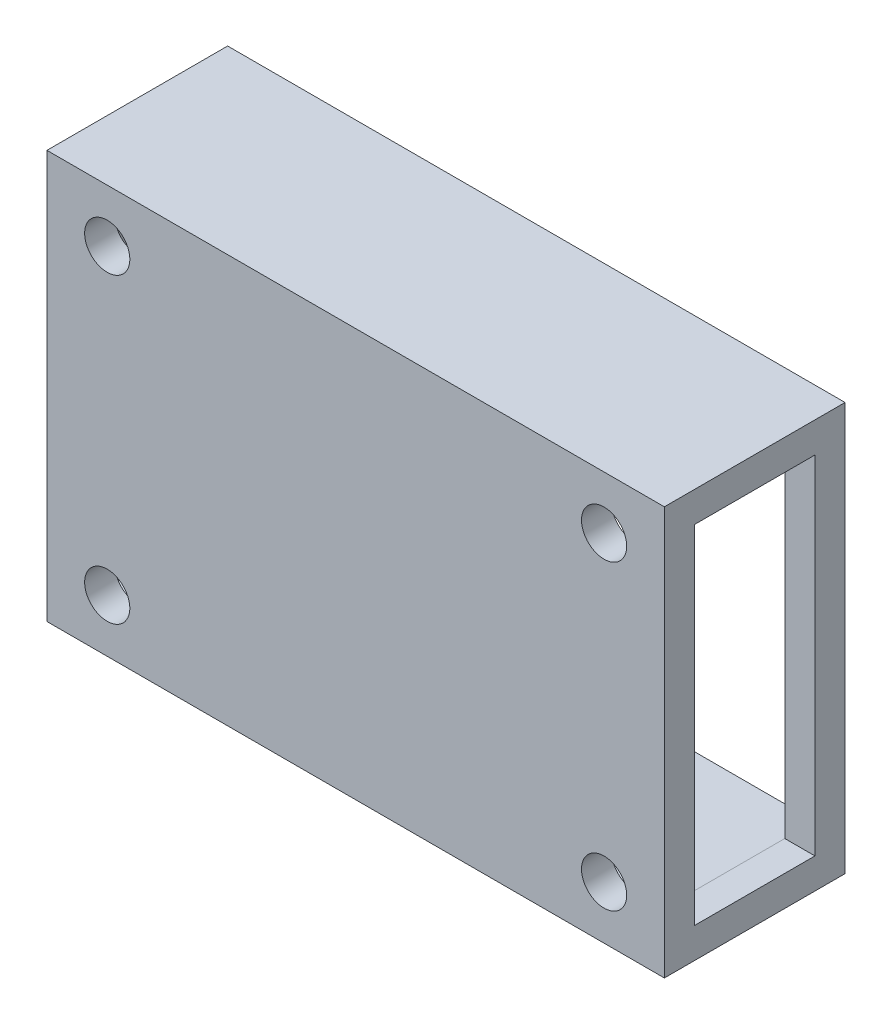
SolidWorks part; units mm, degrees
ref_plane "Plano frontal" through (0, 0, 0) normal (0, 0, 1) x (1, 0, 0)
ref_plane "Plano superior" through (0, 0, 0) normal (0, 1, 0) x (1, 0, 0)
ref_plane "Plano direito" through (0, 0, 0) normal (1, 0, 0) x (0, 0, -1)
sketch "Esboço1" plane through (0, 0, 0) normal (0, 0, 1) x (1, 0, 0)
  line L1 (0, 0) -> (35, 0)
  line L2 (0, 0) -> (0, 25.1)
  line L3 (0, 25.1) -> (35, 25.1)
  line L4 (35, 0) -> (35, 25.1)
extrude "Ressalto-extrusão1" add sketch "Esboço1" along normal blind 2
sketch "Esboço2" plane through (0, 0, 2) normal (0, 0, 1) x (1, 0, 0)
  line L0 (0, 12.55) -> (6.2733, 12.55) construction
  line L2 (0, 25.1) -> (0, 0) construction
  circle A0 centre (2.13, 22.97) radius 1.5
  circle A1 centre (2.13, 2.13) radius 1.5
extrude "Corte-extrusão1" cut sketch "Esboço2" against normal blind 2
sketch "Esboço3" plane through (0, 0, 2) normal (0, 0, 1) x (1, 0, 0)
  line L0 (0, 25.1) -> (-2.0029, 25.1)
  line L1 (-2.0029, 25.1) -> (-2.0029, 0)
  line L2 (-2.0029, 0) -> (0, 0)
  line L3 (0, 0) -> (0, 25.1)
extrude "Ressalto-extrusão2" add sketch "Esboço3" against normal blind 2
sketch "Esboço4" plane through (0, 0, 2) normal (0, 0, 1) x (1, 0, 0)
  line L2 (1.5971, 12.55) -> (1.5971, 19.05)
  line L3 (1.5971, 19.05) -> (14.5971, 19.05)
  line L4 (14.5971, 19.05) -> (14.5971, 6.05)
  line L5 (14.5971, 6.05) -> (1.5971, 6.05)
  line L6 (1.5971, 6.05) -> (1.5971, 12.55)
extrude "Corte-extrusão2" cut sketch "Esboço4" against normal blind 2
sketch "Esboço5" plane through (0, 0, 2) normal (0, 0, 1) x (1, 0, 0)
  line L0 (35, 25.1) -> (39, 25.1)
  line L1 (39, 25.1) -> (39, 0)
  line L2 (39, 0) -> (35, 0)
  line L3 (35, 0) -> (35, 25.1) construction
  line L4 (35, 0) -> (35, 25.1)
extrude "Ressalto-extrusão3" add sketch "Esboço5" against normal blind 2
sketch "Esboço6" plane through (0, 0, 0) normal (0, 0, -1) x (-1, 0, 0)
  line L0 (-39, 25.1) -> (2.0029, 25.1)
  line L1 (2.0029, 25.1) -> (2.0029, 0)
  line L2 (2.0029, 0) -> (-39, 0)
  line L3 (-39, 0) -> (-39, 25.1)
  line L4 (-18.4986, 25.1) -> (-18.4986, 0) construction
  line L5 (-32.9971, 22.1) -> (-4, 22.1)
  line L6 (-4, 3) -> (-32.9971, 3)
  line L7 (-36.9971, 22.1) -> (-36.9971, 3)
  line L10 (0, 22.1) -> (0, 3)
  arc A0 (-4, 22.1) -> (0, 22.1) centre (-2, 22.1) ccw
  arc A1 (-4, 3) -> (0, 3) centre (-2, 3) cw
  arc A2 (-32.9971, 3) -> (-36.9971, 3) centre (-34.9971, 3) ccw
  arc A3 (-32.9971, 22.1) -> (-36.9971, 22.1) centre (-34.9971, 22.1) cw
  point P15 (-18.4986, 3)
  point P25 (-18.4986, 22.1)
extrude "Ressalto-extrusão4" add sketch "Esboço6" along normal blind 10
sketch "Esboço7" plane through (0, 0, 2) normal (0, 0, 1) x (1, 0, 0)
  line L0 (-2.0029, 0) -> (15.3688, 0)
  line L1 (-2.0029, 0) -> (39, 0) construction
  line L2 (15.3688, 0) -> (15.3688, 25.1)
  line L3 (39, 25.1) -> (-2.0029, 25.1) construction
  line L4 (15.3688, 25.1) -> (-2.0029, 25.1)
  line L5 (-2.0029, 25.1) -> (-2.0029, 0)
extrude "Ressalto-extrusão5" add sketch "Esboço7" against normal blind 2
sketch "Esboço8" plane through (0, 0, -10) normal (0, 0, -1) x (-1, 0, 0)
  line L0 (0, 12.55) -> (-5.3416, 12.55) construction
  line L1 (0, 3) -> (0, 22.1) construction
  circle A0 centre (-2, 22.585) radius 1.5
  circle A1 centre (-2, 2.515) radius 1.5
extrude "Corte-extrusão3" cut sketch "Esboço8" against normal blind 20
sketch "Esboço9" plane through (0, 0, -10) normal (0, 0, -1) x (-1, 0, 0)
  line L0 (-2, 20.1) -> (0, 20.1)
  line L1 (0, 3) -> (0, 22.1) construction
  line L2 (0, 20.1) -> (0, 22.1)
  line L3 (2.0029, 12.55) -> (-1.3387, 12.55) construction
  line L4 (2.0029, 0) -> (2.0029, 25.1) construction
  line L5 (0, 5) -> (0, 3)
  line L6 (-2, 5) -> (0, 5)
  arc A0 (-4, 22.1) -> (0, 22.1) centre (-2, 22.1) ccw construction
  arc A1 (0, 22.1) -> (-2, 20.1) centre (-2, 22.1) cw
  arc A2 (0, 3) -> (-2, 5) centre (-2, 3) ccw
extrude "Ressalto-extrusão6" add sketch "Esboço9" against normal blind 10
sketch "Esboço10" plane through (0, 0, -10) normal (0, 0, -1) x (-1, 0, 0)
  line L0 (-34.9971, 20.1) -> (-36.9971, 20.1)
  line L1 (-36.9971, 20.1) -> (-36.9971, 22.1)
  line L2 (-36.9971, 22.1) -> (-34.9971, 20.1)
  line L3 (-36.9971, 3) -> (-34.9971, 3)
  line L4 (-34.9971, 3) -> (-34.9971, 5)
  line L5 (-34.9971, 5) -> (-36.9971, 5)
  line L6 (-36.9971, 22.1) -> (-36.9971, 3) construction
  line L7 (-36.9971, 5) -> (-36.9971, 3)
  arc A0 (-36.9971, 22.1) -> (-32.9971, 22.1) centre (-34.9971, 22.1) ccw construction
  arc A1 (-32.9971, 3) -> (-36.9971, 3) centre (-34.9971, 3) ccw construction
extrude "Ressalto-extrusão7" add sketch "Esboço10" against normal blind 10
sketch "Esboço11" plane through (0, 0, -10) normal (0, 0, -1) x (-1, 0, 0)
  circle A1 centre (-34.9971, 22.585) radius 1.5
  circle A2 centre (-34.9971, 2.515) radius 1.5
extrude "Corte-extrusão4" cut sketch "Esboço11" against normal blind 15
sketch "Esboço12" plane through (0, 0, -10) normal (0, 0, -1) x (-1, 0, 0)
  line L0 (2.0029, 25.1) -> (2.0029, 26.1)
  line L1 (-39, 25.1) -> (-39, 26.1)
  line L2 (-39, 26.1) -> (2.0029, 26.1)
  line L3 (2.0029, 25.1) -> (-39, 25.1)
  line L4 (2.0029, 0) -> (2.0029, -1)
  line L5 (2.0029, -1) -> (-39, -1)
  line L6 (-39, -1) -> (-39, 0)
  line L7 (-39, 0) -> (2.0029, 0)
extrude "Ressalto-extrusão8" add sketch "Esboço12" against normal blind 12
sketch "Esboço13" plane through (0, 0, -10) normal (0, 0, -1) x (-1, 0, 0)
  line L0 (-2, 24.085) -> (0, 24.085)
  line L1 (-2, 1.015) -> (0, 1.015)
  line L2 (0, 24.085) -> (0, 1.015)
  line L4 (-36.9971, 24.085) -> (-36.9971, 1.015)
  line L5 (-36.9971, 1.015) -> (-2, 1.015)
  line L6 (-2, 24.085) -> (-36.9971, 24.085)
  circle A0 centre (-2, 22.585) radius 1.5 construction
  circle A1 centre (-2, 2.515) radius 1.5 construction
extrude "Corte-extrusão5" cut sketch "Esboço13" against normal blind 10
sketch "Esboço14" plane through (39, 0, 0) normal (1, 0, 0) x (0, 0, -1)
  line L8 (8, 24.08) -> (0, 24.08)
  line L14 (8, 1.02) -> (0, 1.02)
  line L15 (0, 1.02) -> (0, 24.08)
  line L16 (8, 24.08) -> (8, 1.02)
  point P12 (0, 12.55)
extrude "Corte-extrusão6" cut sketch "Esboço14" against normal blind 10
